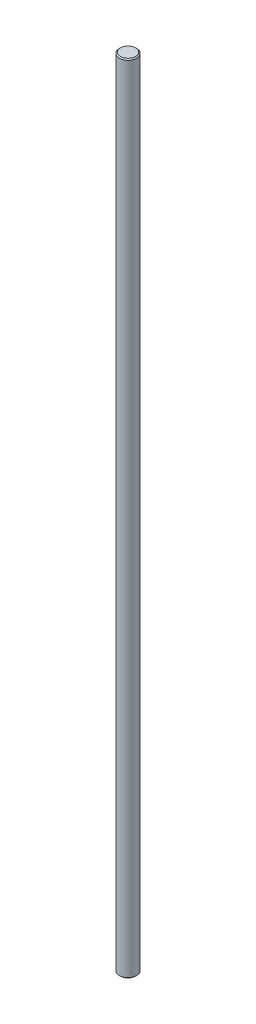
SolidWorks part; units mm, degrees
material "AISI 1020"
ref_plane "Plano frontal" through (0, 0, 0) normal (0, 0, 1) x (1, 0, 0)
ref_plane "Plano superior" through (0, 0, 0) normal (0, 1, 0) x (1, 0, 0)
ref_plane "Plano direito" through (0, 0, 0) normal (1, 0, 0) x (0, 0, -1)
sketch "Esboço3" plane through (0, 0, 0) normal (0, 1, 0) x (1, 0, 0)
  circle A0 centre (0, 0) radius 4
  dimension "D1" = 8
extrude "Ressalto-extrusão1" add sketch "Esboço3" along normal mid plane 370
chamfer "Chanfro1" distance 0.5 angle 45 2 edges at (0, -185, 4) (0, 185, 4)
hole_wizard "Furo roscado de M51" [suppressed] positions "Esboço5" profile "Esboço4" tap size "M5" standard "Din"
sketch "Esboço5" plane through (0, 170, 0) normal (0, 1, 0) x (1, 0, 0)
  circle A0 centre (0, 0) radius 3.5 construction
  point P0 (0, 0)
sketch "Esboço4" plane through (0, 170, 0) normal (1, 0, 0) x (0, 0, 1)
  line L0 (0, 0) -> (0, 25.2618)
  line L1 (0, 25.2618) -> (2.1, 24)
  line L2 (2.1, 24) -> (2.1, 12)
  line L3 (2.1, 12) -> (2.5, 12)
  line L4 (2.5, 12) -> (2.5, 0)
  line L5 (2.5, 0) -> (0, 0)
  line L10 (0, 25.2618) -> (-2.1, 24) construction
  line L11 (0, -6.35) -> (0, 107.95) construction
  dimension "Tap Drill Dia." = 4.2
  dimension "Tap Drill Depth" = 24
  dimension "Thread Major Dia." = 5
  dimension "Thread Depth" = 12
  dimension "Drill Angle" = 118
mirror "Espelhar1" [suppressed] about plane through (0, 0, 0) normal (0, 1, 0)
